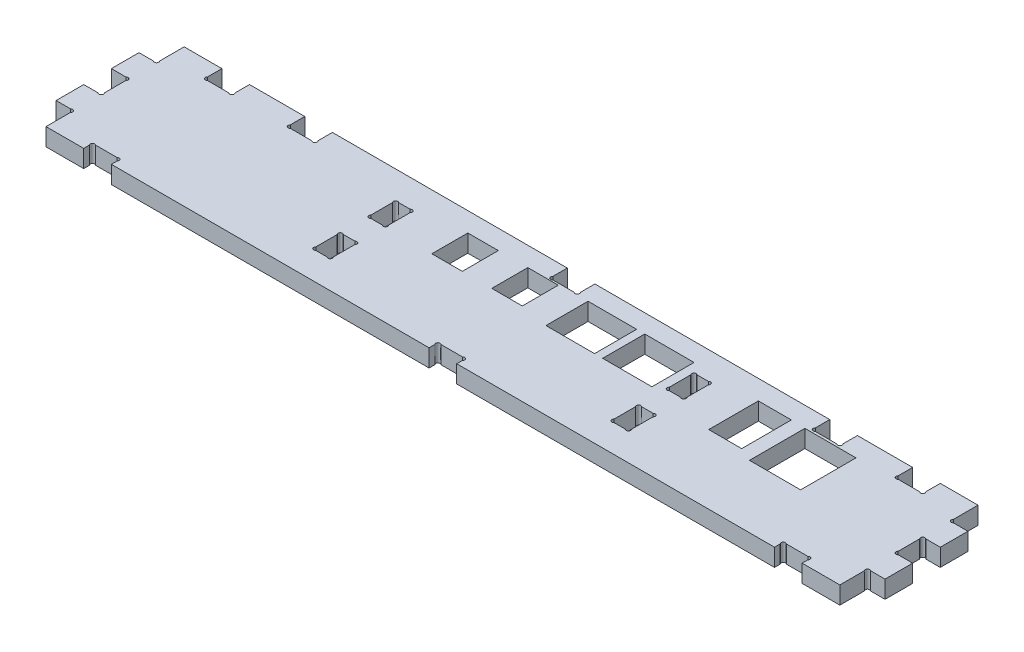
SolidWorks part; units mm, degrees
ref_plane "Front Plane" through (0, 0, 0) normal (0, 0, 1) x (1, 0, 0)
ref_plane "Top Plane" through (0, 0, 0) normal (0, 1, 0) x (1, 0, 0)
ref_plane "Right Plane" through (0, 0, 0) normal (1, 0, 0) x (0, 0, -1)
sketch "Sketch1" plane through (0, 0, 0) normal (0, 1, 0) x (1, 0, 0)
  line L0 (421.513, 20.6475) -> (421.513, 28.4025)
  line L1 (420.3905, 29.525) -> (416.2855, 29.525)
  line L2 (415.163, 28.4025) -> (415.163, 20.6475)
  line L3 (416.2855, 19.525) -> (420.3905, 19.525)
  line L4 (421.513, 40.6475) -> (421.513, 48.4025)
  line L5 (420.3905, 49.525) -> (416.2855, 49.525)
  line L6 (415.163, 48.4025) -> (415.163, 40.6475)
  line L7 (416.2855, 39.525) -> (420.3905, 39.525)
  line L8 (615.95, 18.4025) -> (615.95, 9.525)
  line L9 (615.95, 9.525) -> (602.3, 9.525)
  line L10 (602.3, 9.525) -> (602.3, 11.5775)
  line L11 (601.1775, 12.7) -> (593.4225, 12.7)
  line L12 (592.3, 11.5775) -> (592.3, 9.525)
  line L13 (592.3, 9.525) -> (477.3, 9.525)
  line L14 (477.3, 9.525) -> (477.3, 11.5775)
  line L15 (476.1775, 12.7) -> (468.4225, 12.7)
  line L16 (467.3, 11.5775) -> (467.3, 9.525)
  line L17 (467.3, 9.525) -> (352.3, 9.525)
  line L18 (352.3, 9.525) -> (352.3, 11.5775)
  line L19 (351.1775, 12.7) -> (343.4225, 12.7)
  line L20 (342.3, 11.5775) -> (342.3, 9.525)
  line L21 (342.3, 9.525) -> (328.65, 9.525)
  line L22 (328.65, 9.525) -> (328.65, 18.4025)
  line L23 (327.5275, 19.525) -> (322.3, 19.525)
  line L24 (322.3, 19.525) -> (322.3, 29.525)
  line L25 (322.3, 29.525) -> (327.5275, 29.525)
  line L26 (328.65, 30.6475) -> (328.65, 38.4025)
  line L27 (327.5275, 39.525) -> (322.3, 39.525)
  line L28 (322.3, 39.525) -> (322.3, 49.525)
  line L29 (322.3, 49.525) -> (327.5275, 49.525)
  line L30 (328.65, 50.6475) -> (328.65, 59.525)
  line L31 (328.65, 59.525) -> (342.3, 59.525)
  line L32 (342.3, 59.525) -> (342.3, 54.2975)
  line L33 (343.4225, 53.175) -> (351.1775, 53.175)
  line L34 (352.3, 54.2975) -> (352.3, 59.525)
  line L35 (352.3, 59.525) -> (372.3, 59.525)
  line L36 (372.3, 59.525) -> (372.3, 54.2975)
  line L37 (373.4225, 53.175) -> (381.1775, 53.175)
  line L38 (382.3, 54.2975) -> (382.3, 59.525)
  line L39 (382.3, 59.525) -> (467.3, 59.525)
  line L40 (467.3, 59.525) -> (467.3, 54.2975)
  line L41 (468.4225, 53.175) -> (476.1775, 53.175)
  line L42 (477.3, 54.2975) -> (477.3, 59.525)
  line L43 (477.3, 59.525) -> (562.3, 59.525)
  line L44 (562.3, 59.525) -> (562.3, 54.2975)
  line L45 (563.4225, 53.175) -> (571.1775, 53.175)
  line L46 (572.3, 54.2975) -> (572.3, 59.525)
  line L47 (572.3, 59.525) -> (592.3, 59.525)
  line L48 (592.3, 59.525) -> (592.3, 54.2975)
  line L49 (593.4225, 53.175) -> (601.1775, 53.175)
  line L50 (602.3, 54.2975) -> (602.3, 59.525)
  line L51 (602.3, 59.525) -> (615.95, 59.525)
  line L52 (615.95, 59.525) -> (615.95, 50.6475)
  line L53 (617.0725, 49.525) -> (622.3, 49.525)
  line L54 (622.3, 49.525) -> (622.3, 39.525)
  line L55 (622.3, 39.525) -> (617.0725, 39.525)
  line L56 (615.95, 38.4025) -> (615.95, 30.6475)
  line L57 (617.0725, 29.525) -> (622.3, 29.525)
  line L58 (622.3, 29.525) -> (622.3, 19.525)
  line L59 (622.3, 19.525) -> (617.0725, 19.525)
  line L60 (529.463, 20.6475) -> (529.463, 28.4025)
  line L61 (528.3405, 29.525) -> (524.2355, 29.525)
  line L62 (523.113, 28.4025) -> (523.113, 20.6475)
  line L63 (524.2355, 19.525) -> (528.3405, 19.525)
  line L64 (529.463, 40.6475) -> (529.463, 48.4025)
  line L65 (528.3405, 49.525) -> (524.2355, 49.525)
  line L66 (523.113, 48.4025) -> (523.113, 40.6475)
  line L67 (524.2355, 39.525) -> (528.3405, 39.525)
  line L72 (577.8176, 46.7742) -> (561.8156, 46.7742)
  line L73 (561.8156, 46.7742) -> (561.8156, 33.4392)
  line L74 (561.8156, 33.4392) -> (577.8176, 33.4392)
  line L75 (577.8176, 33.4392) -> (577.8176, 46.7742)
  line L80 (577.8176, 46.7742) -> (561.8156, 46.7742)
  line L81 (561.8156, 46.7742) -> (561.8156, 33.4392)
  line L82 (561.8156, 33.4392) -> (577.8176, 33.4392)
  line L83 (577.8176, 33.4392) -> (577.8176, 46.7742)
  line L88 (503.2684, 38.9002) -> (518.5684, 38.9002)
  line L89 (518.5684, 38.9002) -> (518.5684, 51.6002)
  line L90 (518.5684, 51.6002) -> (503.2684, 51.6002)
  line L91 (503.2684, 51.6002) -> (503.2684, 38.9002)
  line L96 (554.1956, 45.0922) -> (553.9416, 45.0922)
  line L97 (553.9416, 45.0922) -> (553.9416, 46.7742)
  line L98 (553.9416, 46.7742) -> (545.0516, 46.7742)
  line L99 (545.0516, 46.7742) -> (545.0516, 45.0922)
  line L104 (545.0516, 45.0922) -> (544.7976, 45.0922)
  line L105 (544.7976, 45.0922) -> (544.7976, 35.7562)
  line L106 (544.7976, 35.7562) -> (554.1956, 35.7562)
  line L107 (554.1956, 35.7562) -> (554.1956, 45.0922)
  line L108 (554.1956, 45.0922) -> (553.9416, 45.0922)
  line L109 (553.9416, 45.0922) -> (553.9416, 46.7742)
  line L110 (553.9416, 46.7742) -> (545.0516, 46.7742)
  line L111 (545.0516, 46.7742) -> (545.0516, 45.0922)
  line L112 (545.0516, 45.0922) -> (544.7976, 45.0922)
  line L113 (544.7976, 45.0922) -> (544.7976, 35.7562)
  line L114 (544.7976, 35.7562) -> (554.1956, 35.7562)
  line L115 (554.1956, 35.7562) -> (554.1956, 45.0922)
  line L128 (503.2684, 38.9002) -> (518.5684, 38.9002)
  line L129 (518.5684, 38.9002) -> (518.5684, 51.6002)
  line L130 (518.5684, 51.6002) -> (503.2684, 51.6002)
  line L131 (503.2684, 51.6002) -> (503.2684, 38.9002)
  line L132 (482.7426, 38.9002) -> (498.0426, 38.9002)
  line L133 (498.0426, 38.9002) -> (498.0426, 51.6002)
  line L134 (498.0426, 51.6002) -> (482.7426, 51.6002)
  line L135 (482.7426, 51.6002) -> (482.7426, 38.9002)
  line L136 (482.7426, 38.9002) -> (498.0426, 38.9002)
  line L137 (498.0426, 38.9002) -> (498.0426, 51.6002)
  line L138 (498.0426, 51.6002) -> (482.7426, 51.6002)
  line L139 (482.7426, 51.6002) -> (482.7426, 38.9002)
  line L140 (470.0426, 40.5002) -> (470.0426, 51.5002)
  line L141 (470.0426, 51.5002) -> (461.0426, 51.5002)
  line L142 (461.0426, 51.5002) -> (461.0426, 40.5002)
  line L143 (461.0426, 40.5002) -> (470.0426, 40.5002)
  line L144 (470.0426, 40.5002) -> (470.0426, 51.5002)
  line L145 (470.0426, 51.5002) -> (461.0426, 51.5002)
  line L146 (461.0426, 51.5002) -> (461.0426, 40.5002)
  line L147 (461.0426, 40.5002) -> (470.0426, 40.5002)
  line L148 (448.3426, 40.5002) -> (448.3426, 51.5002)
  line L149 (448.3426, 51.5002) -> (439.3426, 51.5002)
  line L150 (439.3426, 51.5002) -> (439.3426, 40.5002)
  line L151 (439.3426, 40.5002) -> (448.3426, 40.5002)
  line L152 (448.3426, 40.5002) -> (448.3426, 51.5002)
  line L153 (448.3426, 51.5002) -> (439.3426, 51.5002)
  line L154 (439.3426, 51.5002) -> (439.3426, 40.5002)
  line L155 (439.3426, 40.5002) -> (448.3426, 40.5002)
  line L209 (449.3586, 52.5162) -> (438.3266, 52.5162)
  line L210 (449.3586, 52.5162) -> (449.3586, 39.4842)
  line L211 (449.3586, 39.4842) -> (438.3266, 39.4842)
  line L212 (438.3266, 52.5162) -> (438.3266, 39.4842)
  line L213 (449.3586, 52.5162) -> (438.3266, 39.4842) construction
  line L214 (449.3586, 39.4842) -> (438.3266, 52.5162) construction
  line L215 (471.0586, 52.5162) -> (460.0266, 52.5162)
  line L216 (471.0586, 52.5162) -> (471.0586, 39.4842)
  line L217 (471.0586, 39.4842) -> (460.0266, 39.4842)
  line L218 (460.0266, 52.5162) -> (460.0266, 39.4842)
  line L219 (471.0586, 52.5162) -> (460.0266, 39.4842) construction
  line L220 (471.0586, 39.4842) -> (460.0266, 52.5162) construction
  line L221 (499.0659, 52.8702) -> (481.4726, 52.8702)
  line L222 (499.0659, 52.8702) -> (499.0659, 37.6302)
  line L223 (499.0659, 37.6302) -> (481.4726, 37.6302)
  line L224 (481.4726, 52.8702) -> (481.4726, 37.6302)
  line L225 (499.0659, 52.8702) -> (481.4726, 37.6302) construction
  line L226 (499.0659, 37.6302) -> (481.4726, 52.8702) construction
  line L227 (579.0546, 32.2194) -> (560.5456, 32.2194)
  line L228 (579.0546, 32.2194) -> (579.0546, 52.268)
  line L229 (579.0546, 52.268) -> (560.5456, 52.268)
  line L230 (560.5456, 32.2194) -> (560.5456, 52.268)
  line L231 (555.4656, 34.4862) -> (543.5276, 34.4862)
  line L232 (555.4656, 34.4862) -> (555.4656, 52.4499)
  line L233 (555.4656, 52.4499) -> (543.5276, 52.4499)
  line L234 (543.5276, 34.4862) -> (543.5276, 52.4499)
  line L235 (519.8384, 37.6302) -> (501.9984, 37.6302)
  line L236 (519.8384, 37.6302) -> (519.8384, 52.8702)
  line L237 (519.8384, 52.8702) -> (501.9984, 52.8702)
  line L238 (501.9984, 37.6302) -> (501.9984, 52.8702)
  arc A0 (421.513, 28.4025) -> (420.3905, 29.525) centre (420.9517, 28.9637) ccw
  arc A1 (416.2855, 29.525) -> (415.163, 28.4025) centre (415.7243, 28.9637) ccw
  arc A2 (415.163, 20.6475) -> (416.2855, 19.525) centre (415.7243, 20.0863) ccw
  arc A3 (420.3905, 19.525) -> (421.513, 20.6475) centre (420.9517, 20.0863) ccw
  arc A4 (421.513, 48.4025) -> (420.3905, 49.525) centre (420.9517, 48.9637) ccw
  arc A5 (416.2855, 49.525) -> (415.163, 48.4025) centre (415.7243, 48.9637) ccw
  arc A6 (415.163, 40.6475) -> (416.2855, 39.525) centre (415.7243, 40.0863) ccw
  arc A7 (420.3905, 39.525) -> (421.513, 40.6475) centre (420.9517, 40.0863) ccw
  arc A8 (602.3, 11.5775) -> (601.1775, 12.7) centre (601.7387, 12.1387) ccw
  arc A9 (593.4225, 12.7) -> (592.3, 11.5775) centre (592.8613, 12.1387) ccw
  arc A10 (477.3, 11.5775) -> (476.1775, 12.7) centre (476.7387, 12.1387) ccw
  arc A11 (468.4225, 12.7) -> (467.3, 11.5775) centre (467.8613, 12.1387) ccw
  arc A12 (352.3, 11.5775) -> (351.1775, 12.7) centre (351.7387, 12.1387) ccw
  arc A13 (343.4225, 12.7) -> (342.3, 11.5775) centre (342.8613, 12.1387) ccw
  arc A14 (328.65, 18.4025) -> (327.5275, 19.525) centre (328.0887, 18.9637) ccw
  arc A15 (327.5275, 29.525) -> (328.65, 30.6475) centre (328.0887, 30.0863) ccw
  arc A16 (328.65, 38.4025) -> (327.5275, 39.525) centre (328.0887, 38.9637) ccw
  arc A17 (327.5275, 49.525) -> (328.65, 50.6475) centre (328.0887, 50.0863) ccw
  arc A18 (342.3, 54.2975) -> (343.4225, 53.175) centre (342.8613, 53.7363) ccw
  arc A19 (351.1775, 53.175) -> (352.3, 54.2975) centre (351.7387, 53.7363) ccw
  arc A20 (372.3, 54.2975) -> (373.4225, 53.175) centre (372.8613, 53.7363) ccw
  arc A21 (381.1775, 53.175) -> (382.3, 54.2975) centre (381.7387, 53.7363) ccw
  arc A22 (467.3, 54.2975) -> (468.4225, 53.175) centre (467.8613, 53.7363) ccw
  arc A23 (476.1775, 53.175) -> (477.3, 54.2975) centre (476.7387, 53.7363) ccw
  arc A24 (562.3, 54.2975) -> (563.4225, 53.175) centre (562.8613, 53.7363) ccw
  arc A25 (571.1775, 53.175) -> (572.3, 54.2975) centre (571.7387, 53.7363) ccw
  arc A26 (592.3, 54.2975) -> (593.4225, 53.175) centre (592.8613, 53.7363) ccw
  arc A27 (601.1775, 53.175) -> (602.3, 54.2975) centre (601.7387, 53.7363) ccw
  arc A28 (615.95, 50.6475) -> (617.0725, 49.525) centre (616.5113, 50.0863) ccw
  arc A29 (617.0725, 39.525) -> (615.95, 38.4025) centre (616.5113, 38.9637) ccw
  arc A30 (615.95, 30.6475) -> (617.0725, 29.525) centre (616.5113, 30.0863) ccw
  arc A31 (617.0725, 19.525) -> (615.95, 18.4025) centre (616.5113, 18.9637) ccw
  arc A32 (529.463, 28.4025) -> (528.3405, 29.525) centre (528.9017, 28.9637) ccw
  arc A33 (524.2355, 29.525) -> (523.113, 28.4025) centre (523.6743, 28.9637) ccw
  arc A34 (523.113, 20.6475) -> (524.2355, 19.525) centre (523.6743, 20.0863) ccw
  arc A35 (528.3405, 19.525) -> (529.463, 20.6475) centre (528.9017, 20.0863) ccw
  arc A36 (529.463, 48.4025) -> (528.3405, 49.525) centre (528.9017, 48.9637) ccw
  arc A37 (524.2355, 49.525) -> (523.113, 48.4025) centre (523.6743, 48.9637) ccw
  arc A38 (523.113, 40.6475) -> (524.2355, 39.525) centre (523.6743, 40.0863) ccw
  arc A39 (528.3405, 39.525) -> (529.463, 40.6475) centre (528.9017, 40.0863) ccw
  point P174 (443.8426, 46.0002)
  point P181 (465.5426, 46.0002)
  point P186 (490.2693, 45.2502)
  point P203 (579.0546, 32.2194)
  point P204 (560.4085, 52.268)
  point P205 (519.483, 53.0962)
  point P206 (502.4047, 37.9733)
  point P207 (499.2519, 37.9733)
  point P208 (499.0659, 53.0962)
  dimension "D7" = 1.27
  dimension "D8" = 1.27
  dimension "D9" = 1.27
  dimension "D10" = 1.27
  dimension "D11" = 1.27
  dimension "D12" = 1.27
  dimension "D13" = 1.27
  dimension "D14" = 1.016
  dimension "D15" = 1.016
  dimension "D16" = 1.016
  dimension "D17" = 1.016
  dimension "D18" = 1.016
  dimension "D19" = 1.016
  dimension "D20" = 1.016
  dimension "D21" = 1.016
  dimension "D22" = 1.2369
  dimension "D23" = 1.27
  dimension "D24" = 1.27
  dimension "D25" = 1.27
  dimension "D26" = 1.27
  dimension "D1" = 0
  dimension "D2" = 0
  dimension "D3" = 0
  dimension "D4" = 0
  dimension "D5" = 0
  dimension "D6" = 0
extrude "Boss-Extrude1" add sketch "Sketch1" along normal blind 6.35 contours A31 L59 L58 L57 A30 L56 A29 L55 L54 L53 A28 L52 L51 L50 A27 L49 A26 L48 L47 L46 A25 L45 A24 L44 L43 L42 A23 L41 A22 L40 L39 L38 A21 L37 A20 L36 L35 L34 A19 L33 A18 L32 L31 L30 A17 L29 L28 L27 A16 L26 A15
